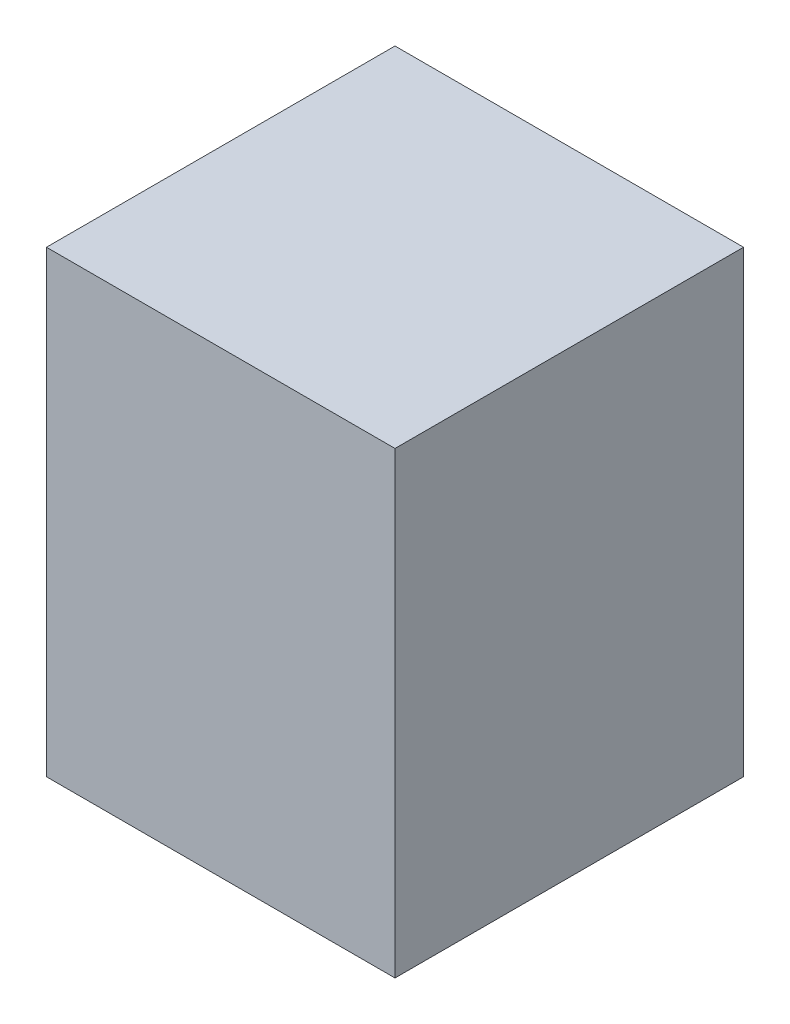
SolidWorks part; units mm, degrees
material "AISI 1020"
ref_plane "Front Plane" through (0, 0, 0) normal (0, 0, 1) x (1, 0, 0)
ref_plane "Top Plane" through (0, 0, 0) normal (0, 1, 0) x (1, 0, 0)
ref_plane "Right Plane" through (0, 0, 0) normal (1, 0, 0) x (0, 0, -1)
sketch "Sketch1" plane through (0, 0, 0) normal (0, 0, 1) x (1, 0, 0)
  line L1 (-24.13, -31.75) -> (24.13, -31.75)
  line L2 (-24.13, -31.75) -> (-24.13, 31.75)
  line L3 (-24.13, 31.75) -> (24.13, 31.75)
  line L4 (24.13, -31.75) -> (24.13, 31.75)
  line L5 (-24.13, -31.75) -> (24.13, 31.75) construction
  line L6 (-24.13, 31.75) -> (24.13, -31.75) construction
  point P0 (0, 0)
  dimension "D1" = 63.5
  dimension "D2" = 48.26
extrude "Boss-Extrude1" add sketch "Sketch1" along normal mid plane 48.26
sketch "Sketch2" plane through (0, 0, 24.13) normal (0, 0, 1) x (1, 0, 0)
  line L0 (-24.13, 13.97) -> (24.13, 13.97) construction
  line L1 (-24.13, 31.75) -> (-24.13, -31.75) construction
  line L2 (24.13, -31.75) -> (24.13, 31.75) construction
  line L3 (-24.13, -31.75) -> (24.13, -31.75) construction
  dimension "D1" = 45.72
ref_plane "Plane1" through (0, -6.7414, 9.6277) normal (0, -0.5736, 0.8192) x (1, 0, 0)
ref_point "Point1"
ref_plane "Plane2" through (0, -8.1983, 11.7084) normal (0, -0.5736, 0.8192) x (1, 0, 0)
